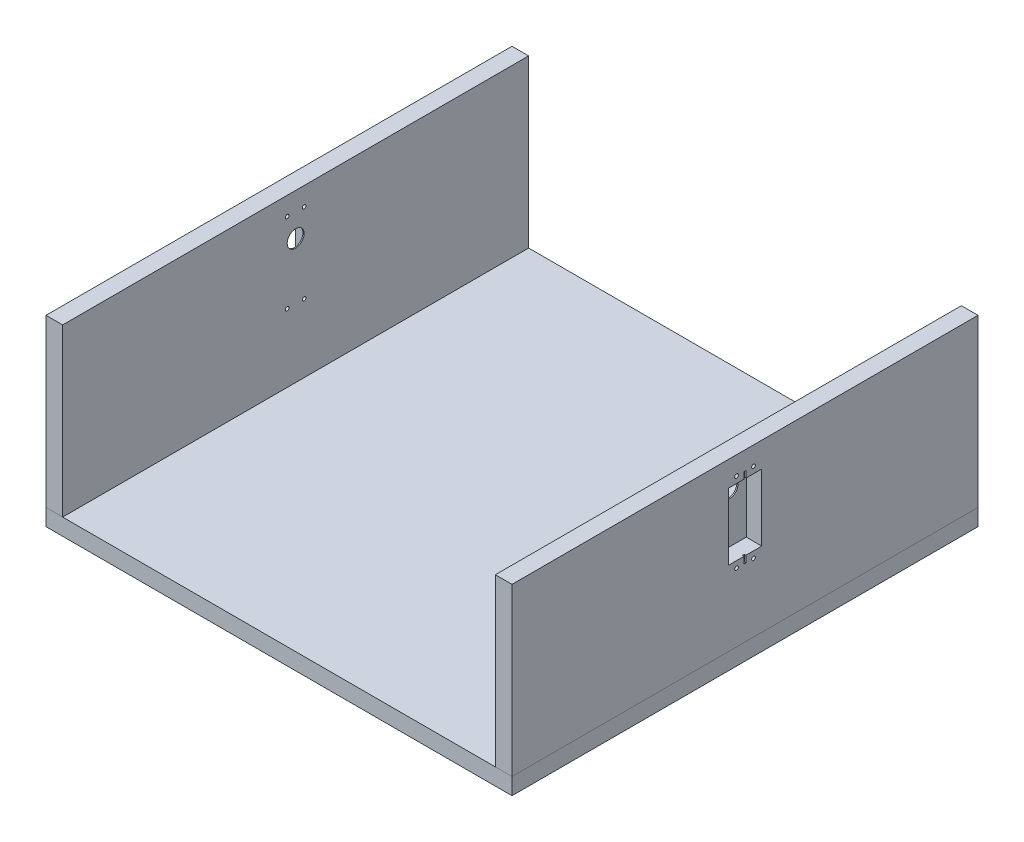
SolidWorks part; units mm, degrees
ref_plane "Front Plane" through (0, 0, 0) normal (0, 0, 1) x (1, 0, 0)
ref_plane "Top Plane" through (0, 0, 0) normal (0, 1, 0) x (1, 0, 0)
ref_plane "Right Plane" through (0, 0, 0) normal (1, 0, 0) x (0, 0, -1)
sketch "Sketch1" plane through (0, 0, 0) normal (0, 1, 0) x (1, 0, 0)
  line L1 (-140, -140) -> (140, -140)
  line L2 (-140, -140) -> (-140, 140)
  line L3 (-140, 140) -> (140, 140)
  line L4 (140, -140) -> (140, 140)
  line L5 (-140, -140) -> (140, 140) construction
  line L6 (-140, 140) -> (140, -140) construction
  point P0 (0, 0)
  dimension "D2" = 280
extrude "Boss-Extrude1" add sketch "Sketch1" along normal blind 10
sketch "Sketch3" plane through (0, 10, 0) normal (0, 1, 0) x (1, 0, 0)
  line L0 (140, 140) -> (-140, 140) construction
  line L1 (140, 140) -> (130, 140)
  line L2 (140, 140) -> (140, -140)
  line L3 (140, -140) -> (130, -140)
  line L4 (130, 140) -> (130, -140)
  line L5 (140, -140) -> (140, 140) construction
  line L6 (-140, -140) -> (140, -140) construction
  line L12 (-140, 140) -> (-130, 140)
  line L13 (-140, 140) -> (-140, -140)
  line L14 (-140, -140) -> (-130, -140)
  line L15 (-130, 140) -> (-130, -140)
  dimension "D1" = 10
  dimension "D2" = 10
extrude "Boss-Extrude2" add sketch "Sketch3" along normal blind 100
sketch "Sketch4" plane through (140, 0, 0) normal (1, 0, 0) x (0, 0, -1)
  line L1 (-140, 110) -> (140, 110) construction
  line L3 (-10.06, 54.88) -> (10.06, 54.88)
  line L4 (-10.06, 54.88) -> (-10.06, 95)
  line L5 (-10.06, 95) -> (10.06, 95)
  line L6 (10.06, 54.88) -> (10.06, 95)
  line L7 (-10.06, 54.88) -> (10.06, 95) construction
  line L8 (-10.06, 95) -> (10.06, 54.88) construction
  point P0 (0, 74.94)
  point P8 (0, 110)
  dimension "D1" = 20.12
  dimension "D2" = 40.12
  dimension "D3" = 15
extrude "Cut-Extrude2" cut sketch "Sketch4" against normal blind 9.3
sketch "Sketch8" plane through (140, 0, 0) normal (1, 0, 0) x (0, 0, -1)
  line L0 (0, 55) -> (0, -55) construction
  line L1 (-0.55, 50.88) -> (0.55, 50.88)
  line L2 (-0.55, 50.88) -> (-0.55, 99)
  line L3 (-0.55, 99) -> (0.55, 99)
  line L4 (0.55, 50.88) -> (0.55, 99)
  line L5 (-0.55, 50.88) -> (0.55, 99) construction
  line L6 (-0.55, 99) -> (0.55, 50.88) construction
  line L10 (10.06, 95) -> (-10.06, 95) construction
  line L11 (-10.06, 95) -> (-10.06, 54.88) construction
  point P0 (0, 74.94)
  point P14 (-10.06, 74.94)
  dimension "D1" = 4
  dimension "D2" = 1.1
extrude "Cut-Extrude5" cut sketch "Sketch8" against normal blind 1
sketch "Sketch5" plane through (130.7, 0, 0) normal (1, 0, 0) x (0, 0, -1)
  line L0 (10.06, 95) -> (-10.06, 95) construction
  circle A0 centre (0, 85) radius 5.075
  point P6 (0, 95)
  dimension "D1" = 10.15
  dimension "D2" = 10
extrude "Cut-Extrude3" cut sketch "Sketch5" against normal blind 10
ref_plane "Plane1" through (0, 0, 0) normal (0, 0, 1) x (1, 0, 0)
ref_plane "Plane2" through (0, 74.94, 0) normal (0, -1, 0) x (-1, 0, 0)
sketch "Sketch7" plane through (140, 0, 0) normal (1, 0, 0) x (0, 0, -1)
  line L1 (0, 5.115) -> (0, -5.115) construction
  line L2 (-5.115, 74.94) -> (5.115, 74.94) construction
  circle A0 centre (-5.1, 98.9) radius 1.125
  circle A1 centre (0, 85) radius 5.075 construction
  circle A2 centre (5.1, 98.9) radius 1.125
  circle A3 centre (5.1, 50.98) radius 1.125
  circle A4 centre (-5.1, 50.98) radius 1.125
  dimension "D1" = 2.25
  dimension "D3" = 5.1
  dimension "D2" = 13.9
extrude "Cut-Extrude4" cut sketch "Sketch7" against normal blind 20
mirror "Mirror1" about plane through (0, 0, 0) normal (1, 0, 0) of "Cut-Extrude5", "Cut-Extrude2", "Cut-Extrude3", "Cut-Extrude4"
